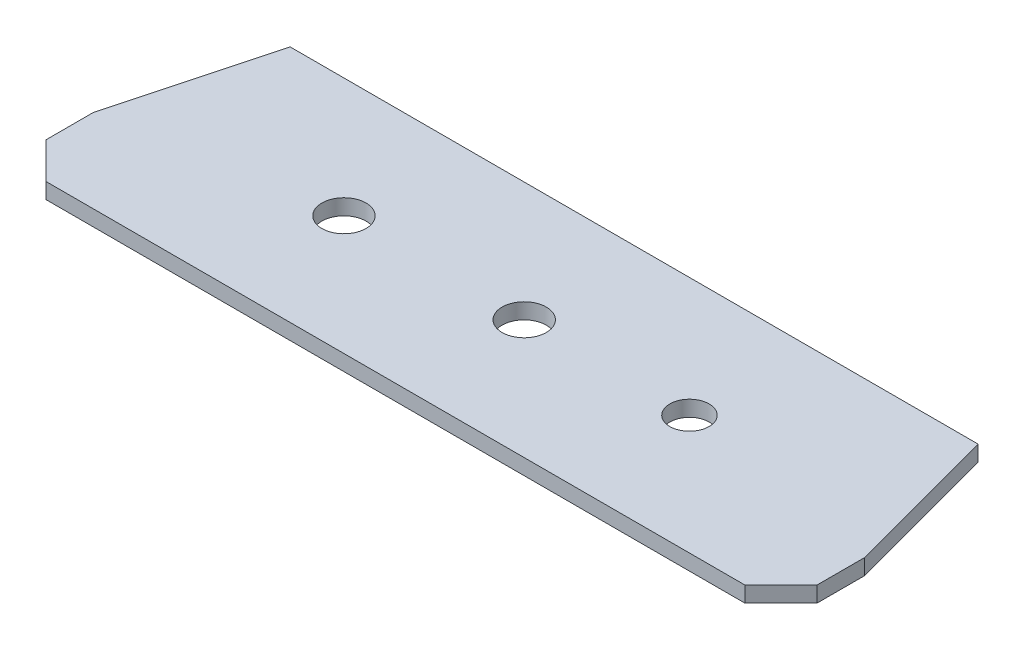
SolidWorks part; units mm, degrees
ref_plane "Front Plane" through (0, 0, 0) normal (0, 0, 1) x (1, 0, 0)
ref_plane "Top Plane" through (0, 0, 0) normal (0, 1, 0) x (1, 0, 0)
ref_plane "Right Plane" through (0, 0, 0) normal (1, 0, 0) x (0, 0, -1)
sketch "Sketch1" plane through (0, 0, 0) normal (0, 1, 0) x (1, 0, 0)
  line L0 (54.991, -19.304) -> (60.833, -13.462)
  line L1 (-58.039, -19.304) -> (54.991, -19.304)
  line L2 (60.833, -13.462) -> (60.833, -5.8267)
  line L3 (-57.15, 19.2938) -> (54.102, 19.2938)
  line L4 (60.833, -5.8267) -> (54.102, 19.2938)
  line L5 (54.102, 19.2938) -> (53.8628, 19.2701)
  line L6 (-63.881, -5.8267) -> (-57.15, 19.2938)
  line L7 (-63.881, -13.462) -> (-63.881, -5.8267)
  line L8 (54.991, -19.304) -> (62.357, -11.938) construction
  line L9 (63.963, -17.508) -> (54.102, 19.2938) construction
  line L10 (-58.039, -19.304) -> (-63.881, -13.462)
  line L11 (60.833, 19.304) -> (60.833, -19.304) construction
  line L15 (-1.524, 19.2938) -> (-1.524, -19.304) construction
  point P0 (0, 0)
  dimension "D1" = 38.608
  dimension "D2" = 111.252
  dimension "D3" = 62.357
  dimension "D4" = 105
  dimension "D6" = 135
extrude "Boss-Extrude1" add sketch "Sketch1" along normal blind 2.54
sketch "Sketch2" plane through (0, 2.54, 0) normal (0, 1, 0) x (1, 0, 0)
  line L0 (-1.524, -19.304) -> (-56.769, -19.304) construction
  line L1 (-58.039, -19.304) -> (54.991, -19.304) construction
  line L2 (-29.1465, -19.304) -> (-29.1465, 19.2938) construction
  line L3 (-57.15, 19.2938) -> (54.102, 19.2938) construction
  line L4 (-1.524, -19.304) -> (54.991, -19.304) construction
  line L5 (54.991, -19.304) -> (26.7335, -19.304)
  line L6 (26.7335, -19.304) -> (26.7335, 19.2938) construction
  circle A0 centre (0, 0) radius 3.5719
  circle A1 centre (-29.1465, -0.0051) radius 3.5719
  circle A2 centre (26.7335, -0.0051) radius 3.175
  dimension "D1" = 7.1437
  dimension "D3" = 7.1437
  dimension "D4" = 6.35
extrude "Cut-Extrude4" cut sketch "Sketch2" against normal through all contours A1 | A0 | A2
